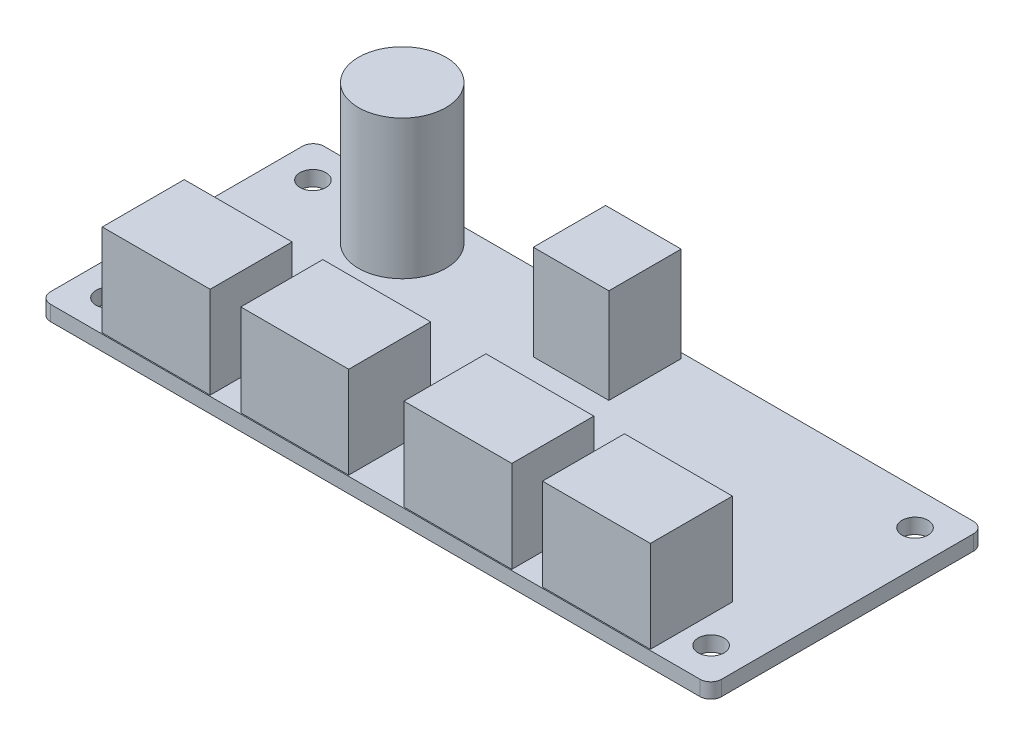
SolidWorks part; units mm, degrees
ref_plane "Front" through (0, 0, 0) normal (0, 0, 1) x (1, 0, 0)
ref_plane "Top" through (0, 0, 0) normal (0, 1, 0) x (1, 0, 0)
ref_plane "Right" through (0, 0, 0) normal (1, 0, 0) x (0, 0, -1)
sketch "Sketch1" plane through (0, 0, 0) normal (0, 1, 0) x (1, 0, 0)
  line L1 (-30.1, -12.675) -> (30.1, -12.675)
  line L2 (-31.1, -11.675) -> (-31.1, 11.675)
  line L3 (-30.1, 12.675) -> (30.1, 12.675)
  line L4 (31.1, -11.675) -> (31.1, 11.675)
  line L5 (-31.1, -12.675) -> (31.1, 12.675) construction
  line L6 (-31.1, 12.675) -> (31.1, -12.675) construction
  line L7 (-27.9, -9.45) -> (27.9, -9.45) construction
  line L8 (-27.9, -9.45) -> (-27.9, 9.45) construction
  line L9 (-27.9, 9.45) -> (27.9, 9.45) construction
  line L10 (27.9, -9.45) -> (27.9, 9.45) construction
  line L11 (-27.9, -9.45) -> (27.9, 9.45) construction
  line L12 (-27.9, 9.45) -> (27.9, -9.45) construction
  arc A0 (-30.1, -12.675) -> (-31.1, -11.675) centre (-30.1, -11.675) cw
  arc A1 (30.1, -12.675) -> (31.1, -11.675) centre (30.1, -11.675) ccw
  arc A2 (30.1, 12.675) -> (31.1, 11.675) centre (30.1, 11.675) cw
  arc A3 (-31.1, 11.675) -> (-30.1, 12.675) centre (-30.1, 11.675) cw
  circle A4 centre (-27.9, 9.45) radius 1.2
  circle A5 centre (-27.9, -9.45) radius 1.2
  circle A6 centre (27.9, -9.45) radius 1.2
  circle A7 centre (27.9, 9.45) radius 1.2
  point P0 (0, 0)
  point P18 (0, 0)
  dimension "D3" = 1
  dimension "D4" = 2.4
  dimension "D1" = 25.35
  dimension "D2" = 62.2
  dimension "D5" = 55.8
  dimension "D6" = 18.9
extrude "Boss-Extrude1" add sketch "Sketch1" along normal blind 1.4
sketch "Sketch2" plane through (0, 1.4, 0) normal (0, 1, 0) x (1, 0, 0)
  line L0 (30.1, 12.675) -> (-30.1, 12.675) construction
  line L1 (-3.5, 5.475) -> (3.5, 5.475)
  line L2 (-3.5, 5.475) -> (-3.5, 12.175)
  line L3 (-3.5, 12.175) -> (3.5, 12.175)
  line L4 (3.5, 5.475) -> (3.5, 12.175)
  line L5 (-3.5, 5.475) -> (3.5, 12.175) construction
  line L6 (-3.5, 12.175) -> (3.5, 5.475) construction
  point P0 (0, 8.825)
  dimension "D1" = 0.5
  dimension "D2" = 6.7
  dimension "D3" = 7
extrude "Boss-Extrude2" add sketch "Sketch2" along normal blind 8.8
sketch "Sketch3" plane through (0, 1.4, 0) normal (0, 1, 0) x (1, 0, 0)
  line L0 (-25.4, -8.775) -> (25.4, -8.775) construction
  line L1 (-25.4, -12.575) -> (-15.4, -12.575)
  line L2 (-25.4, -12.575) -> (-25.4, -4.975)
  line L3 (-25.4, -4.975) -> (-15.4, -4.975)
  line L4 (-15.4, -12.575) -> (-15.4, -4.975)
  line L5 (-25.4, -12.575) -> (-15.4, -4.975) construction
  line L6 (-25.4, -4.975) -> (-15.4, -12.575) construction
  line L7 (-12.56, -12.575) -> (-2.56, -12.575)
  line L8 (-12.56, -12.575) -> (-12.56, -4.975)
  line L9 (-12.56, -4.975) -> (-2.56, -4.975)
  line L10 (-2.56, -12.575) -> (-2.56, -4.975)
  line L11 (-12.56, -12.575) -> (-2.56, -4.975) construction
  line L12 (-12.56, -4.975) -> (-2.56, -12.575) construction
  line L13 (-30.1, -12.675) -> (30.1, -12.675) construction
  point P0 (-20.4, -8.775)
  point P5 (-7.56, -8.775)
  point P13 (0, -8.775)
  dimension "D1" = 50.8
  dimension "D2" = 10
  dimension "D3" = 7.6
  dimension "D4" = 0.1
  dimension "D5" = 2.84
extrude "Boss-Extrude3" add sketch "Sketch3" along normal blind 8.5
mirror "Mirror1" about plane through (0, 0, 0) normal (1, 0, 0) of "Boss-Extrude3"
sketch "Sketch4" plane through (0, 1.4, 0) normal (0, 1, 0) x (1, 0, 0)
  line L0 (-31.1, 11.675) -> (-31.1, -11.675) construction
  line L1 (30.1, 12.675) -> (-30.1, 12.675) construction
  circle A0 centre (-18.7, 8.525) radius 4.05
  dimension "D2" = 8.1
  dimension "D1" = 12.4
  dimension "D3" = 4.15
extrude "Boss-Extrude4" add sketch "Sketch4" along normal blind 12.9
